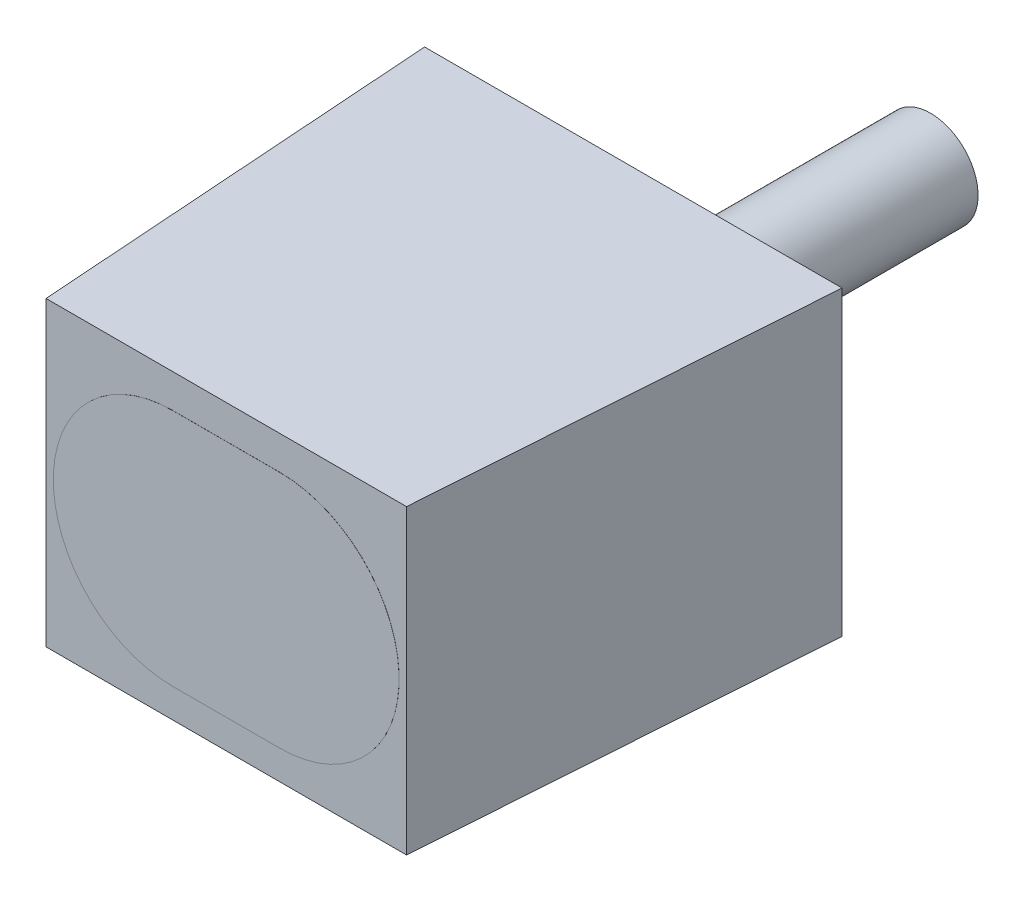
SolidWorks part; units mm, degrees
ref_plane "Front" through (0, 0, 0) normal (0, 0, 1) x (1, 0, 0)
ref_plane "Top" through (0, 0, 0) normal (0, 1, 0) x (1, 0, 0)
ref_plane "Right" through (0, 0, 0) normal (1, 0, 0) x (0, 0, -1)
sketch "Sketch1" plane through (0, 0, 0) normal (0, 1, 0) x (1, 0, 0)
  line L0 (-19, -21.45) -> (-22, 21.45)
  line L1 (22, -21.45) -> (-22, -21.45)
  line L2 (22, -21.45) -> (22, 21.45)
  line L3 (22, 21.45) -> (-22, 21.45)
  line L4 (-22, -21.45) -> (-22, 21.45)
  line L5 (22, -21.45) -> (-22, 21.45) construction
  line L6 (22, 21.45) -> (-22, -21.45) construction
  line L7 (0, 24.6676) -> (0, -26.7132) construction
  line L8 (19, -21.45) -> (22, 21.45)
  point P0 (0, 0)
  dimension "D1" = 42.9
  dimension "D2" = 44
  dimension "D3" = 3
extrude "Boss-Extrude1" add sketch "Sketch1" along normal blind 31.8 contours L3 L4 L1 L2
sketch "Sketch2" plane through (0, 31.8, 0) normal (0, 1, 0) x (1, 0, 0)
  line L0 (0, 22.6994) -> (0, -22.879) construction
  line L1 (-22, 21.45) -> (-19, -21.45)
  line L2 (22, 21.45) -> (-22, 21.45) construction
  line L3 (-22, -21.45) -> (-22, 21.45) construction
  line L4 (22, -21.45) -> (-22, -21.45) construction
  line L5 (22, 21.45) -> (19, -21.45)
  line L6 (-22, 21.45) -> (22, 21.45)
  line L7 (-19, -21.45) -> (19, -21.45)
  dimension "D1" = 3
extrude "Cut-Extrude1" cut sketch "Sketch2" against normal blind 31.8 flip side to cut
sketch "Sketch6" plane through (0, 0, -21.45) normal (0, 0, -1) x (-1, 0, 0)
  circle A0 centre (0.4675, 15.6195) radius 5
  dimension "D1" = 10
extrude "Boss-Extrude2" add sketch "Sketch6" along normal blind 31.8 contours A0
sketch "Sketch7" plane through (0, 0, 21.45) normal (0, 0, 1) x (1, 0, 0)
  line L0 (5.6342, 15.6663) -> (-5.6342, 15.6663) construction
  line L1 (5.6342, 3.0787) -> (-5.6342, 3.0787)
  line L2 (5.6342, 28.2538) -> (-5.6342, 28.2538)
  line L3 (-19, 0) -> (-19, 31.8) construction
  arc A0 (5.6342, 3.0787) -> (5.6342, 28.2538) centre (5.6342, 15.6663) ccw
  arc A1 (-5.6342, 28.2538) -> (-5.6342, 3.0787) centre (-5.6342, 15.6663) ccw
  point P2 (0, 15.6663)
  point P7 (0, 0)
  point P8 (0, 0)
  point P13 (0, 0)
  dimension "D1" = 19
extrude "Boss-Extrude3" add sketch "Sketch7" along normal blind 0.01
